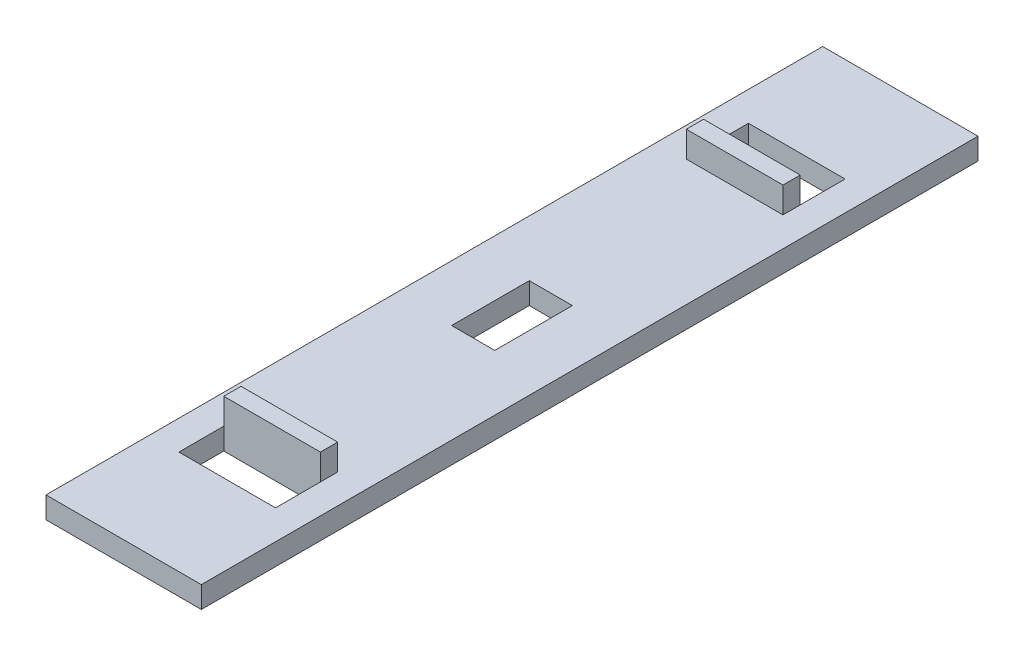
SolidWorks part; units mm, degrees
ref_plane "Plan de face" through (0, 0, 0) normal (0, 0, 1) x (1, 0, 0)
ref_plane "Plan de dessus" through (0, 0, 0) normal (0, 1, 0) x (1, 0, 0)
ref_plane "Plan de droite" through (0, 0, 0) normal (1, 0, 0) x (0, 0, -1)
sketch "Esquisse1" plane through (0, 0, 0) normal (0, 1, 0) x (1, 0, 0)
  line L0 (3.409, -1.8775) -> (3.409, 4.1225) construction
  line L1 (-1.091, 43.1225) -> (7.909, 43.1225)
  line L2 (-1.091, 43.1225) -> (-1.091, -1.8775)
  line L3 (-1.091, -1.8775) -> (7.909, -1.8775)
  line L4 (7.909, 43.1225) -> (7.909, -1.8775)
  line L5 (0.609, 4.1225) -> (6.209, 4.1225)
  line L6 (0.609, 4.1225) -> (0.609, 6.7225)
  line L7 (0.609, 6.7225) -> (6.209, 6.7225)
  line L8 (6.209, 4.1225) -> (6.209, 6.7225)
  line L9 (-1.091, 20.6225) -> (7.909, 20.6225) construction
  line L10 (0.609, 34.5225) -> (6.209, 34.5225)
  line L11 (6.209, 37.1225) -> (6.209, 34.5225)
  line L12 (0.609, 37.1225) -> (6.209, 37.1225)
  line L13 (0.609, 37.1225) -> (0.609, 34.5225)
  dimension "D1" = 45
  dimension "D2" = 9
  dimension "D3" = 6
  dimension "D4" = 5.6
  dimension "D5" = 2.6
extrude "Boss.-Extru.1" add sketch "Esquisse1" along normal blind 1.25 contours L4 L1 L2 L3 L13 L12 L11 L10 L8 L5 L6 L7
sketch "Esquisse2" plane through (0, 0, 0) normal (0, -1, 0) x (1, 0, 0)
  line L0 (-1.091, -20.6225) -> (7.909, -20.6225) construction
  line L1 (-1.091, -43.1225) -> (-1.091, 1.8775) construction
  line L2 (7.909, -43.1225) -> (7.909, 1.8775) construction
  line L4 (4.659, -22.8725) -> (2.159, -22.8725)
  line L5 (4.659, -22.8725) -> (4.659, -18.3725)
  line L6 (4.659, -18.3725) -> (2.159, -18.3725)
  line L7 (2.159, -22.8725) -> (2.159, -18.3725)
  line L8 (4.659, -22.8725) -> (2.159, -18.3725) construction
  line L9 (4.659, -18.3725) -> (2.159, -22.8725) construction
  point P6 (3.409, -20.6225)
  point P11 (3.409, -20.6225)
  dimension "D1" = 4.5
  dimension "D2" = 2.5
extrude "Enlèv. mat.-Extru.1" cut sketch "Esquisse2" along normal through all and the other way through all contours L7 L4 L5 L6
sketch "Esquisse3" plane through (0, 1.25, 0) normal (0, 1, 0) x (1, 0, 0)
  line L0 (0.609, 6.7225) -> (6.209, 6.7225)
  line L1 (0.609, 6.7225) -> (0.609, 7.7225)
  line L2 (6.209, 6.7225) -> (6.209, 7.7225)
  line L3 (0.609, 7.7225) -> (6.209, 7.7225)
  line L4 (-1.091, 20.6225) -> (7.909, 20.6225) construction
  line L5 (-1.091, 43.1225) -> (-1.091, -1.8775) construction
  line L6 (7.909, 43.1225) -> (7.909, -1.8775) construction
  line L7 (6.209, 34.5225) -> (6.209, 33.5225)
  line L8 (0.609, 33.5225) -> (6.209, 33.5225)
  line L9 (0.609, 34.5225) -> (0.609, 33.5225)
  line L10 (0.609, 34.5225) -> (6.209, 34.5225)
  dimension "D1" = 1
extrude "Boss.-Extru.2" add sketch "Esquisse3" along normal blind 1.5
